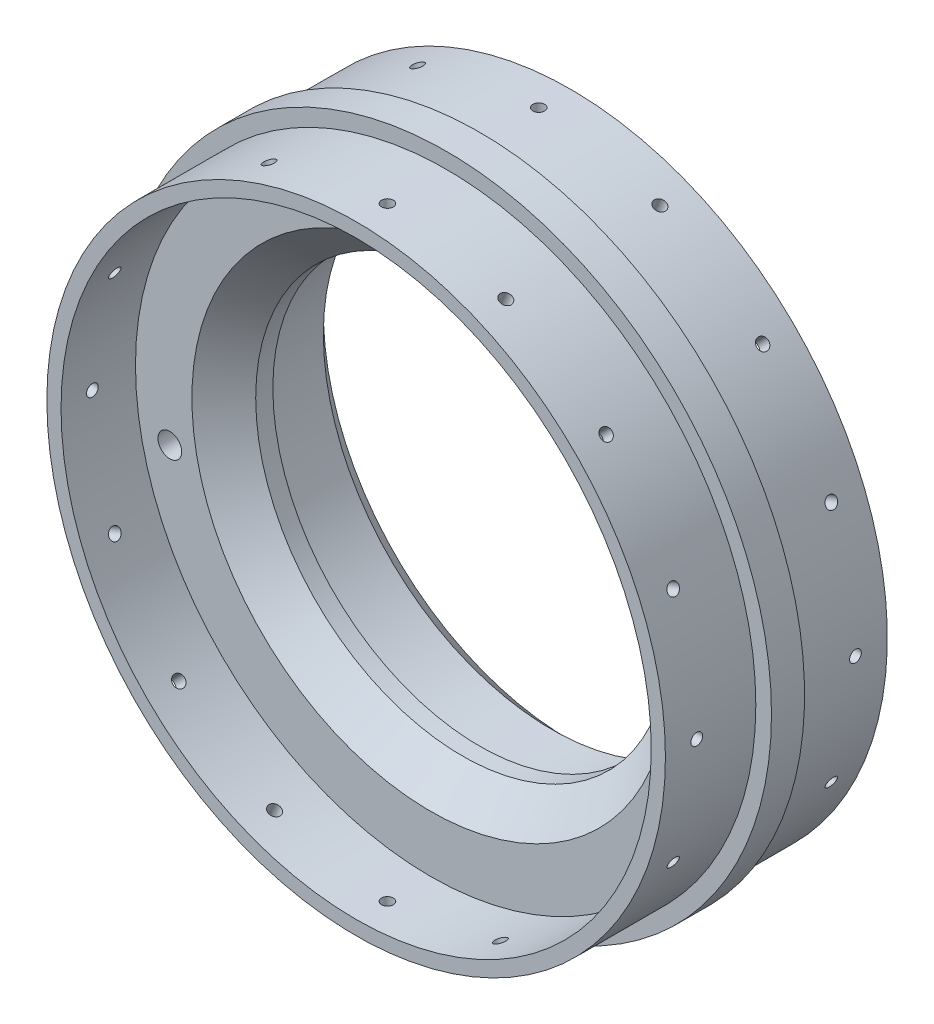
SolidWorks part; units mm, degrees
material "6061-T6 (SS)"
ref_plane "Front Plane" through (0, 0, 0) normal (0, 0, 1) x (1, 0, 0)
ref_plane "Top Plane" through (0, 0, 0) normal (0, 1, 0) x (1, 0, 0)
ref_plane "Right Plane" through (0, 0, 0) normal (1, 0, 0) x (0, 0, -1)
sketch "Sketch5" plane through (0, 0, 0) normal (0, 0, 1) x (1, 0, 0)
  circle A0 centre (0, 0) radius 69.85
extrude "Extrude1" add sketch "Sketch5" along normal blind 46.101
sketch "Sketch8" plane through (0, 0, 46.101) normal (0, 0, 1) x (1, 0, 0)
  circle A0 centre (0, 0) radius 44.45
extrude "Extrude4" cut sketch "Sketch8" against normal through all
sketch "Sketch6" plane through (0, 0, 46.101) normal (0, 0, 1) x (1, 0, 0)
  circle A0 centre (0, 0) radius 66.4845
extrude "Extrude2" cut sketch "Sketch6" against normal blind 19.431 flip side to cut
sketch "Sketch7" plane through (0, 0, 46.101) normal (0, 0, 1) x (1, 0, 0)
  circle A0 centre (0, 0) radius 63.4365
extrude "Extrude3" cut sketch "Sketch7" against normal blind 16.002
chamfer "Chamfer1" distance 6.858 distance2 6.858 1 edges at (44.45, 0, 30.099)
sketch "Sketch9" plane through (0, 0, 0) normal (0, 0, -1) x (-1, 0, 0)
  circle A0 centre (0, 0) radius 68.0847
extrude "Extrude5" cut sketch "Sketch9" against normal blind 19.558 flip side to cut
sketch "Sketch10" plane through (0, 0, 0) normal (0, 0, -1) x (-1, 0, 0)
  circle A0 centre (0, 0) radius 65.0367
  circle A1 centre (0, 0) radius 53.7845
extrude "Extrude6" cut sketch "Sketch10" against normal blind 9.525
sketch "Sketch11" plane through (0, 0, 0) normal (0, 0, -1) x (-1, 0, 0)
  circle A0 centre (0, 0) radius 49.0855
extrude "Extrude7" cut sketch "Sketch11" against normal blind 19.558
chamfer "Chamfer2" distance 4.064 angle 45 1 edges at (-49.0855, 0, 0)
ref_plane "Plane1" through (0, 0, 39.37) normal (0, 0, 1) x (1, 0, 0)
ref_plane "Plane2" through (0, 0, 6.858) normal (0, 0, -1) x (-1, 0, 0)
sketch "Sketch13" plane through (0, 0, 6.858) normal (0, 0, -1) x (-1, 0, 0)
  line L0 (0, 0) -> (0, 68.0847) construction
  circle A0 centre (0, 0) radius 68.0847 construction
ref_plane "Plane3" through (0, 68.0847, 6.858) normal (0, 1, 0) x (-1, 0, 0)
sketch "Sketch15" plane through (0, 0, 39.37) normal (0, 0, 1) x (1, 0, 0)
  line L0 (0, 0) -> (0, 66.4845) construction
  line L1 (0, 0) -> (0, 68.0847) construction
  circle A0 centre (0, 0) radius 66.4845 construction
ref_plane "Plane4" through (0, 66.4845, 39.37) normal (0, 1, 0) x (-1, 0, 0)
hole_wizard "#39 (0.0995) Diameter Hole2" positions "Sketch20" profile "Sketch19" hole size "#39" standard "Ansi Inch"
sketch "Sketch20" plane through (0, 68.0847, 6.858) normal (0, 1, 0) x (-1, 0, 0)
  point P1 (0, 0)
sketch "Sketch19" plane through (0, 68.0847, 6.858) normal (1, 0, 0) x (0, 0, 1)
  line L0 (0, 0) -> (0, 13.4593)
  line L1 (0, 13.4593) -> (1.2636, 12.7)
  line L2 (1.2636, 12.7) -> (1.2636, 0)
  line L5 (1.2636, 0) -> (0, 0)
  line L10 (0, 13.4593) -> (-1.2636, 12.7) construction
  line L11 (0, -6.35) -> (0, 107.95) construction
  dimension "Hole Dia." = 2.5273
  dimension "Hole Depth" = 12.7
  dimension "Drill Angle" = 118
hole_wizard "#39 (0.0995) Diameter Hole6" positions "Sketch26" profile "Sketch25" hole size "#39" standard "Ansi Inch"
sketch "Sketch26" plane through (0, 66.4845, 39.37) normal (0, 1, 0) x (-1, 0, 0)
  point P1 (0, 0)
sketch "Sketch25" plane through (0, 66.4845, 39.37) normal (1, 0, 0) x (0, 0, 1)
  line L0 (0, 0) -> (0, 13.4593)
  line L1 (0, 13.4593) -> (1.2636, 12.7)
  line L2 (1.2636, 12.7) -> (1.2636, 0)
  line L5 (1.2636, 0) -> (0, 0)
  line L10 (0, 13.4593) -> (-1.2636, 12.7) construction
  line L11 (0, -6.35) -> (0, 107.95) construction
  dimension "Hole Dia." = 2.5273
  dimension "Hole Depth" = 12.7
  dimension "Drill Angle" = 118
pattern_circular "CirPattern1" count 16 over 360 about axis through (0, 0, 19.558) along (0, 0, -1) of "#39 (0.0995) Diameter Hole2", "#39 (0.0995) Diameter Hole6"
ref_plane "Plane5" through (0, 0, 23.114) normal (0, 0, 1) x (1, 0, 0)
sketch "Sketch27" plane through (0, 0, 23.114) normal (0, 0, 1) x (1, 0, 0)
  line L0 (0, -65.0367) -> (0, -68.0847) construction
  arc A0 (0, -69.85) -> (13.6271, -68.5079) centre (0, 0) ccw construction
  circle A1 centre (0, 0) radius 69.85 construction
ref_plane "Plane6" through (13.6271, -68.5079, 23.114) normal (0.1951, -0.9808, 0) x (0.9808, 0.1951, 0)
hole_wizard "#21 (0.159) Diameter Hole1" positions "Sketch29" profile "Sketch28" hole size "#21" standard "Ansi Inch"
sketch "Sketch29" plane through (13.6271, -68.5079, 23.114) normal (0.1951, -0.9808, 0) x (0.9808, 0.1951, 0)
  point P1 (0, 0)
sketch "Sketch28" plane through (13.6271, -68.5079, 23.114) normal (0, 0, 1) x (0.9808, 0.1951, 0)
  line L0 (0, 0) -> (0, 13.9133)
  line L1 (0, 13.9133) -> (2.0193, 12.7)
  line L2 (2.0193, 12.7) -> (2.0193, 0)
  line L5 (2.0193, 0) -> (0, 0)
  line L10 (0, 13.9133) -> (-2.0193, 12.7) construction
  line L11 (0, -6.35) -> (0, 107.95) construction
  dimension "Hole Dia." = 4.0386
  dimension "Hole Depth" = 12.7
  dimension "Drill Angle" = 118
sketch "Sketch30" plane through (0, 0, 30.099) normal (0, 0, 1) x (1, 0, 0)
  arc A0 (0, -57.15) -> (56.0519, 11.1494) centre (0, 0) ccw construction
hole_wizard "#7 (0.201) Diameter Hole1" positions "3DSketch1" profile "Sketch31" hole size "#7" standard "Ansi Inch" end condition through all
sketch3d "3DSketch1"
  point P0 (56.0519, 11.1494, 30.099)
sketch "Sketch31" plane through (56.0519, 11.1494, 30.099) normal (1, 0, 0) x (0, -1, 0)
  line L0 (0, 0) -> (0, 30.099)
  line L1 (0, 30.099) -> (2.5527, 30.099)
  line L2 (2.5527, 30.099) -> (2.5527, 0)
  line L5 (2.5527, 0) -> (0, 0)
  line L11 (0, -6.35) -> (0, 107.95) construction
  dimension "Thru Hole Dia." = 5.1054
  dimension "Thru Hole Depth" = 30.099
pattern_circular "CirPattern2" count 2 over 360 about axis through (0, 0, 0) along (0, 0, 1) of "#7 (0.201) Diameter Hole1"
